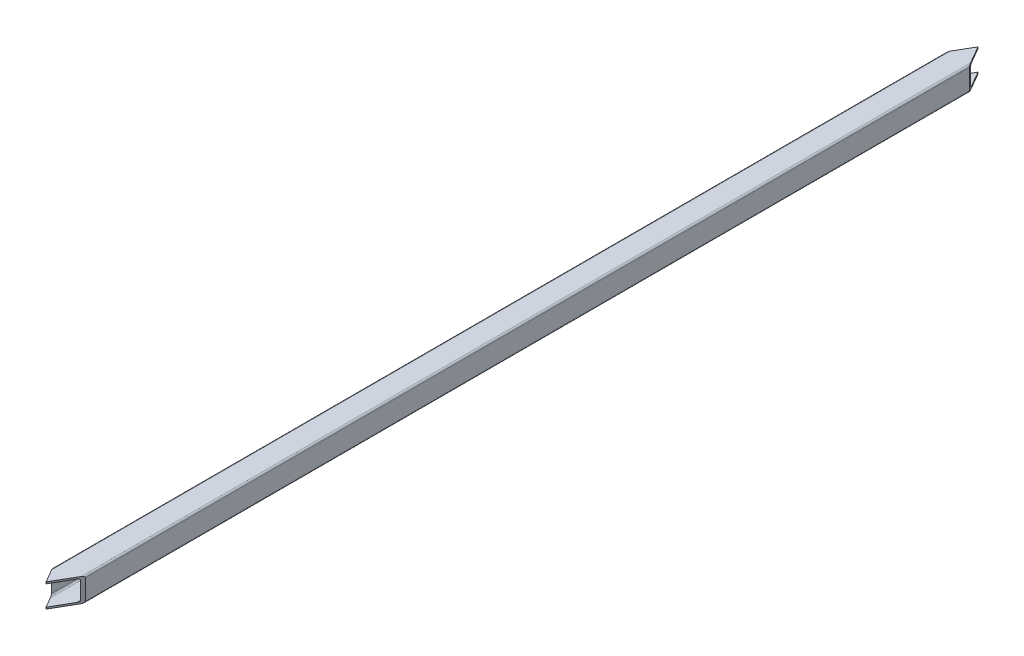
SolidWorks part; units mm, degrees
material "ASTM A500 Grade B"
ref_plane "Front Plane" through (0, 0, 0) normal (0, 0, 1) x (1, 0, 0)
ref_plane "Top Plane" through (0, 0, 0) normal (0, 1, 0) x (1, 0, 0)
ref_plane "Right Plane" through (0, 0, 0) normal (1, 0, 0) x (0, 0, -1)
sketch "Sketch1" plane through (0, 0, 0) normal (0, 0, 1) x (1, 0, 0)
  line L0 (5.3086, -2.7686) -> (32.7914, -2.7686)
  line L1 (2.54, 0) -> (35.56, 0)
  line L2 (0, -2.54) -> (0, -35.56)
  line L3 (2.54, -38.1) -> (35.56, -38.1)
  line L4 (38.1, -2.54) -> (38.1, -35.56)
  line L5 (35.3314, -5.3086) -> (35.3314, -32.7914)
  line L6 (5.3086, -35.3314) -> (32.7914, -35.3314)
  line L7 (2.7686, -5.3086) -> (2.7686, -32.7914)
  line L8 (0, 0) -> (0, -38.1) construction
  line L9 (0, -38.1) -> (38.1, -38.1) construction
  line L10 (38.1, 0) -> (38.1, -38.1) construction
  line L11 (2.7686, -2.7686) -> (2.7686, -35.3314) construction
  line L12 (2.7686, -35.3314) -> (35.3314, -35.3314) construction
  line L13 (35.3314, -2.7686) -> (35.3314, -35.3314) construction
  line L14 (2.7686, -2.7686) -> (35.3314, -2.7686) construction
  line L15 (0, 0) -> (38.1, 0) construction
  arc A0 (0, -35.56) -> (2.54, -38.1) centre (2.54, -35.56) ccw
  arc A1 (38.1, -35.56) -> (35.56, -38.1) centre (35.56, -35.56) cw
  arc A2 (2.7686, -32.7914) -> (5.3086, -35.3314) centre (5.3086, -32.7914) ccw
  arc A3 (32.7914, -35.3314) -> (35.3314, -32.7914) centre (32.7914, -32.7914) ccw
  arc A4 (35.3314, -5.3086) -> (32.7914, -2.7686) centre (32.7914, -5.3086) ccw
  arc A5 (38.1, -2.54) -> (35.56, 0) centre (35.56, -2.54) ccw
  arc A6 (0, -2.54) -> (2.54, 0) centre (2.54, -2.54) cw
  arc A7 (5.3086, -2.7686) -> (2.7686, -5.3086) centre (5.3086, -5.3086) ccw
  point P12 (0, -38.1)
  dimension "D4" = 2.54
  dimension "D3" = 2.7686
extrude "Boss-Extrude1" add sketch "Sketch1" along normal blind 1500
sketch "Sketch2" plane through (0, 0, 0) normal (0, 1, 0) x (1, 0, 0)
  line L0 (19.05, 0) -> (38.1, -32.9956)
  line L1 (35.56, 0) -> (2.54, 0) construction
  line L2 (38.1, -1500) -> (38.1, 0) construction
  line L3 (38.1, -32.9956) -> (38.1, 0)
  line L4 (38.1, 0) -> (19.05, 0)
  line L5 (0, -1500) -> (0, -1474.2875)
  line L6 (0, -1500) -> (0, 0) construction
  line L7 (0, -1474.2875) -> (14.8451, -1500)
  line L8 (35.56, -1500) -> (2.54, -1500) construction
  line L9 (14.8451, -1500) -> (0, -1500)
  dimension "D1" = 30
  dimension "D2" = 30
extrude "Cut-Extrude1" cut sketch "Sketch2" against normal through all both and the other way through all
sketch "Sketch3" plane through (0, -38.1, 0) normal (0, -1, 0) x (1, 0, 0)
  line L0 (14.8451, 1500) -> (38.1, 1459.7214)
  line L1 (38.1, 1500) -> (38.1, 32.9956) construction
  line L2 (19.05, 0) -> (0, 32.9956)
  line L3 (0, 1474.2875) -> (0, 0) construction
  line L4 (0, 32.9956) -> (0, 0)
  line L5 (0, 0) -> (19.05, 0)
  line L6 (35.56, 1500) -> (14.8451, 1500)
  line L7 (14.8451, 1500) -> (2.54, 1478.6869)
  line L8 (2.54, 1478.6869) -> (2.54, 0)
  line L9 (2.54, 0) -> (19.05, 0)
  line L10 (19.05, 0) -> (35.56, 28.5962)
  line L11 (35.56, 28.5962) -> (35.56, 1500)
  line L12 (35.56, 1500) -> (14.8451, 1500)
  line L13 (14.8451, 1500) -> (2.54, 1478.6869)
  line L14 (2.54, 1478.6869) -> (2.54, 0)
  line L15 (2.54, 0) -> (19.05, 0)
  line L16 (19.05, 0) -> (35.56, 28.5962)
  line L17 (35.56, 28.5962) -> (35.56, 1500)
  line L18 (35.56, 1500) -> (38.1, 1500)
  line L19 (38.1, 1500) -> (38.1, 1459.7214)
  line M10 (35.56, 1500) -> (14.8451, 1500)
  line M12 (2.54, 1478.6869) -> (2.54, 0)
  line M13 (2.54, 0) -> (19.05, 0)
  line M15 (35.56, 28.5962) -> (35.56, 1500)
  dimension "D2" = 60
  dimension "D3" = 60
  dimension "D1" = 0
extrude "Cut-Extrude2" cut sketch "Sketch3" against normal through all both and the other way through all contours L0 M10 M15 | L19 L18 L0 M15 | L4 L5 L2 M12 | L2 M13 M12
